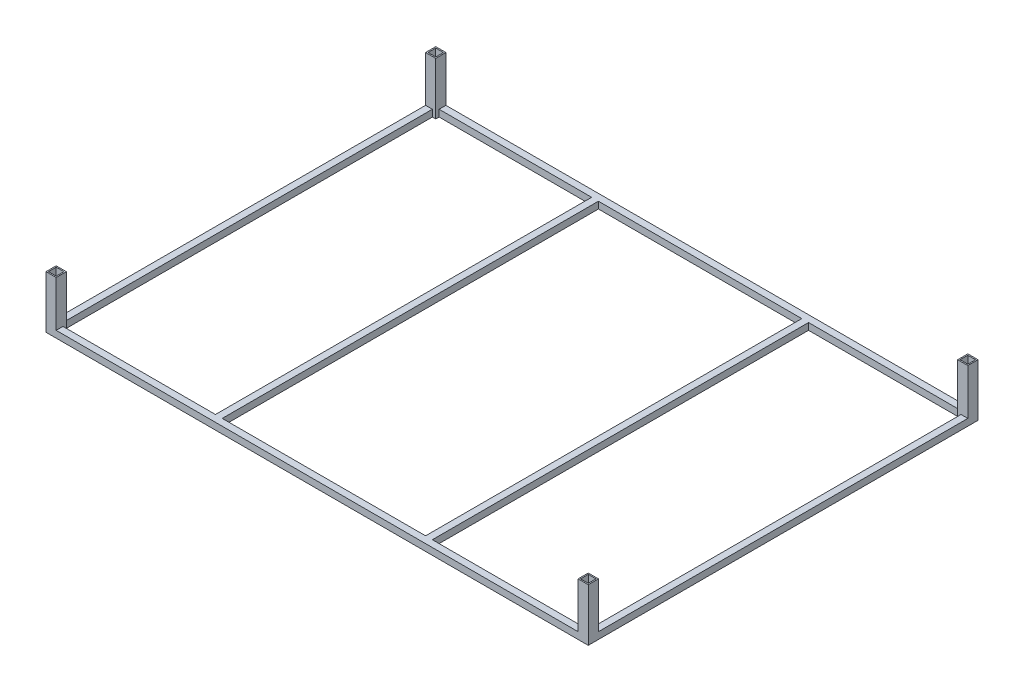
SolidWorks part; units mm, degrees
ref_plane "Front Plane" through (0, 0, 0) normal (0, 0, 1) x (1, 0, 0)
ref_plane "Top Plane" through (0, 0, 0) normal (0, 1, 0) x (1, 0, 0)
ref_plane "Right Plane" through (0, 0, 0) normal (1, 0, 0) x (0, 0, -1)
sketch "Sketch1" plane through (0, 0, 0) normal (1, 0, 0) x (0, 0, -1)
  line L1 (2300, -310) -> (2220, -310)
  line L2 (2300, -310) -> (2300, -230)
  line L3 (2300, -230) -> (2220, -230)
  line L4 (2220, -310) -> (2220, -230)
  line L6 (2297, -307) -> (2223, -307)
  line L7 (2297, -307) -> (2297, -233)
  line L8 (2297, -233) -> (2223, -233)
  line L9 (2223, -307) -> (2223, -233)
extrude "Boss-Extrude1" add sketch "Sketch1" along normal blind 6400 from offset 3200
sketch "Sketch2" plane through (0, 0, 0) normal (1, 0, 0) x (0, 0, -1)
  line L1 (-2220, -310) -> (-2300, -310)
  line L2 (-2220, -310) -> (-2220, -230)
  line L3 (-2220, -230) -> (-2300, -230)
  line L4 (-2300, -310) -> (-2300, -230)
  line L6 (-2223, -307) -> (-2297, -307)
  line L7 (-2223, -307) -> (-2223, -233)
  line L8 (-2223, -233) -> (-2297, -233)
  line L9 (-2297, -307) -> (-2297, -233)
extrude "Boss-Extrude2" add sketch "Sketch2" along normal blind 6400 from offset 3200
sketch "Sketch3" plane through (0, 0, 0) normal (0, 0, 1) x (1, 0, 0)
  line L1 (-3200, -310) -> (-3120, -310)
  line L2 (-3200, -310) -> (-3200, -230)
  line L3 (-3200, -230) -> (-3120, -230)
  line L4 (-3120, -310) -> (-3120, -230)
  line L6 (-3197, -307) -> (-3123, -307)
  line L7 (-3197, -307) -> (-3197, -233)
  line L8 (-3197, -233) -> (-3123, -233)
  line L9 (-3123, -307) -> (-3123, -233)
extrude "Boss-Extrude3" add sketch "Sketch3" along normal blind 4440 from offset 2220
sketch "Sketch4" plane through (0, 0, 0) normal (0, 0, 1) x (1, 0, 0)
  line L1 (-1280, -310) -> (-1200, -310)
  line L2 (-1280, -310) -> (-1280, -230)
  line L3 (-1280, -230) -> (-1200, -230)
  line L4 (-1200, -310) -> (-1200, -230)
  line L6 (-1277, -307) -> (-1203, -307)
  line L7 (-1277, -307) -> (-1277, -233)
  line L8 (-1277, -233) -> (-1203, -233)
  line L9 (-1203, -307) -> (-1203, -233)
extrude "Boss-Extrude4" add sketch "Sketch4" along normal blind 4440 from offset 2220
sketch "Sketch5" plane through (0, 0, 0) normal (0, 0, 1) x (1, 0, 0)
  line L1 (3120, -310) -> (3200, -310)
  line L2 (3120, -310) -> (3120, -230)
  line L3 (3120, -230) -> (3200, -230)
  line L4 (3200, -310) -> (3200, -230)
  line L6 (3123, -307) -> (3197, -307)
  line L7 (3123, -307) -> (3123, -233)
  line L8 (3123, -233) -> (3197, -233)
  line L9 (3197, -307) -> (3197, -233)
extrude "Boss-Extrude5" add sketch "Sketch5" along normal blind 4440 from offset 2220
sketch "Sketch6" plane through (0, 0, 0) normal (0, 0, 1) x (1, 0, 0)
  line L1 (1200, -310) -> (1280, -310)
  line L2 (1200, -310) -> (1200, -230)
  line L3 (1200, -230) -> (1280, -230)
  line L4 (1280, -310) -> (1280, -230)
  line L6 (1203, -307) -> (1277, -307)
  line L7 (1203, -307) -> (1203, -233)
  line L8 (1203, -233) -> (1277, -233)
  line L9 (1277, -307) -> (1277, -233)
extrude "Boss-Extrude6" add sketch "Sketch6" along normal blind 4440 from offset 2220
sketch "Sketch7" plane through (0, 0, 0) normal (0, 1, 0) x (1, 0, 0)
  line L1 (-3200, 2300) -> (-3080, 2300)
  line L2 (-3200, 2300) -> (-3200, 2180)
  line L3 (-3200, 2180) -> (-3080, 2180)
  line L4 (-3080, 2300) -> (-3080, 2180)
  line L6 (-3185.7035, 2285.7035) -> (-3094.2965, 2285.7035)
  line L7 (-3185.7035, 2285.7035) -> (-3185.7035, 2194.2965)
  line L8 (-3185.7035, 2194.2965) -> (-3094.2965, 2194.2965)
  line L9 (-3094.2965, 2285.7035) -> (-3094.2965, 2194.2965)
extrude "Boss-Extrude7" add sketch "Sketch7" along normal blind 620 from offset 310
sketch "Sketch8" plane through (0, 0, 0) normal (0, 1, 0) x (1, 0, 0)
  line L1 (-3200, -2180) -> (-3080, -2180)
  line L2 (-3200, -2180) -> (-3200, -2300)
  line L3 (-3200, -2300) -> (-3080, -2300)
  line L4 (-3080, -2180) -> (-3080, -2300)
  line L6 (-3185.7035, -2194.2965) -> (-3094.2965, -2194.2965)
  line L7 (-3185.7035, -2194.2965) -> (-3185.7035, -2285.7035)
  line L8 (-3185.7035, -2285.7035) -> (-3094.2965, -2285.7035)
  line L9 (-3094.2965, -2194.2965) -> (-3094.2965, -2285.7035)
extrude "Boss-Extrude8" add sketch "Sketch8" along normal blind 620 from offset 310
sketch "Sketch9" plane through (0, 0, 0) normal (0, 1, 0) x (1, 0, 0)
  line L1 (3080, 2300) -> (3200, 2300)
  line L2 (3080, 2300) -> (3080, 2180)
  line L3 (3080, 2180) -> (3200, 2180)
  line L4 (3200, 2300) -> (3200, 2180)
  line L6 (3094.2965, 2285.7035) -> (3185.7035, 2285.7035)
  line L7 (3094.2965, 2285.7035) -> (3094.2965, 2194.2965)
  line L8 (3094.2965, 2194.2965) -> (3185.7035, 2194.2965)
  line L9 (3185.7035, 2285.7035) -> (3185.7035, 2194.2965)
extrude "Boss-Extrude9" add sketch "Sketch9" along normal blind 620 from offset 310
sketch "Sketch10" plane through (0, 0, 0) normal (0, 1, 0) x (1, 0, 0)
  line L1 (3080, -2180) -> (3200, -2180)
  line L2 (3080, -2180) -> (3080, -2300)
  line L3 (3080, -2300) -> (3200, -2300)
  line L4 (3200, -2180) -> (3200, -2300)
  line L6 (3094.2965, -2194.2965) -> (3185.7035, -2194.2965)
  line L7 (3094.2965, -2194.2965) -> (3094.2965, -2285.7035)
  line L8 (3094.2965, -2285.7035) -> (3185.7035, -2285.7035)
  line L9 (3185.7035, -2194.2965) -> (3185.7035, -2285.7035)
extrude "Boss-Extrude10" add sketch "Sketch10" along normal blind 620 from offset 310
